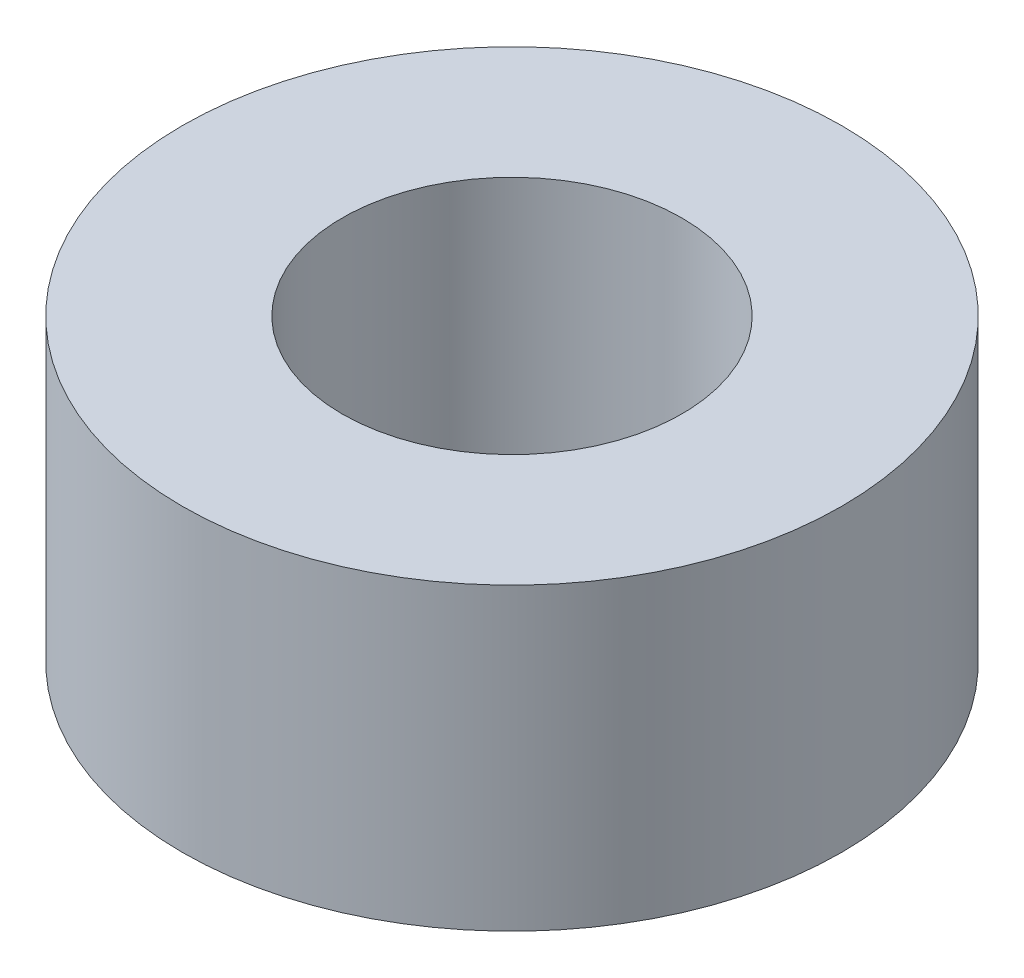
SolidWorks part; units mm, degrees
ref_plane "Front Plane" through (0, 0, 0) normal (0, 0, 1) x (1, 0, 0)
ref_plane "Top Plane" through (0, 0, 0) normal (0, 1, 0) x (1, 0, 0)
ref_plane "Right Plane" through (0, 0, 0) normal (1, 0, 0) x (0, 0, -1)
sketch "Sketch1" plane through (0, 0, 0) normal (0, 1, 0) x (1, 0, 0)
  circle A0 centre (0, 0) radius 3.3
  dimension "D1" = 6.6
extrude "Boss-Extrude1" add sketch "Sketch1" along normal blind 3
hole_wizard "M3 Clearance Hole1" positions "Sketch2" profile "Sketch3" hole size "M3" standard "ISO" end condition through all
sketch "Sketch2" plane through (0, 3, 0) normal (0, 1, 0) x (1, 0, 0)
  point P0 (0, 0)
sketch "Sketch3" plane through (0, 3, 0) normal (1, 0, 0) x (0, 0, 1)
  line L0 (0, 0) -> (0, 3)
  line L1 (0, 3) -> (1.7, 3)
  line L2 (1.7, 3) -> (1.7, 0)
  line L5 (1.7, 0) -> (0, 0)
  line L11 (0, -6.35) -> (0, 107.95) construction
  dimension "Thru Hole Dia." = 3.4
  dimension "Thru Hole Depth" = 3
